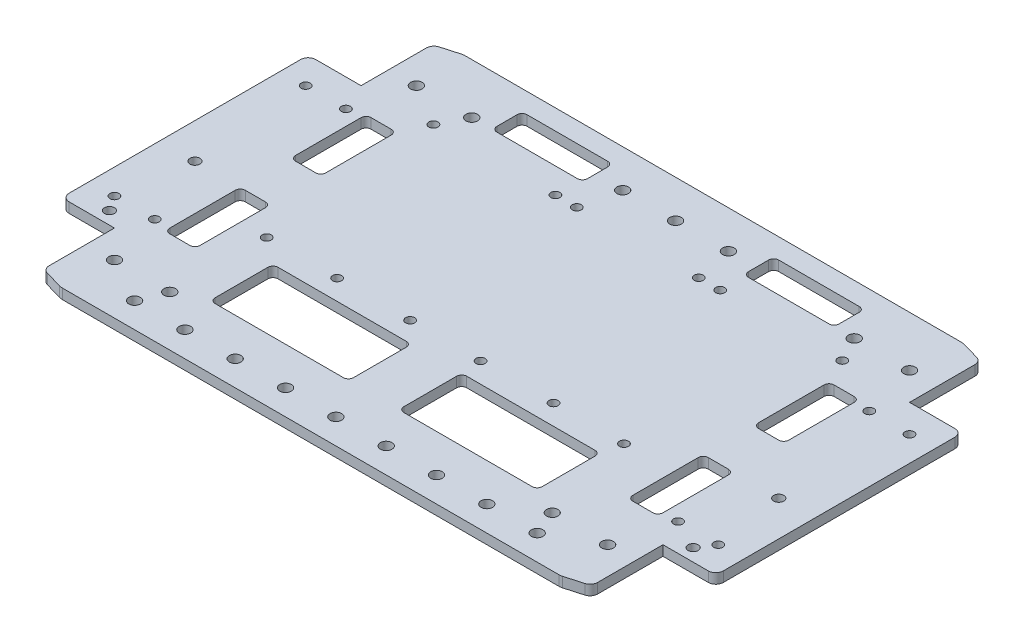
SolidWorks part; units mm, degrees
ref_plane "Plan de face" through (0, 0, 0) normal (0, 0, 1) x (1, 0, 0)
ref_plane "Plan de dessus" through (0, 0, 0) normal (0, 1, 0) x (1, 0, 0)
ref_plane "Plan de droite" through (0, 0, 0) normal (1, 0, 0) x (0, 0, -1)
sketch "Esquisse1" plane through (0, 0, 0) normal (0, 1, 0) x (1, 0, 0)
  line L0 (0, 0) -> (135, 0) construction
  line L1 (0, 0) -> (-135, 0) construction
  line L2 (-135, 0) -> (-135, -75)
  line L3 (-135, -85) -> (135, -85) construction
  line L4 (135, 0) -> (135, 75)
  line L5 (0, 85) -> (0, -85) construction
  line L6 (135, 85) -> (-135, 85) construction
  line L24 (0, -85) -> (-100, -85)
  line L26 (0, -85) -> (100, -85)
  line L28 (135, 0) -> (135, -75)
  line L31 (0, 85) -> (-100, 85)
  line L32 (0, 85) -> (100, 85)
  line L34 (-135, 0) -> (-135, 75)
  line L35 (-135, -75) -> (-100, -85)
  line L37 (-135, 75) -> (-100, 85)
  line L38 (100, 85) -> (135, 75)
  line L39 (100, -85) -> (135, -75)
  line L40 (-135, 75) -> (-100, 75) construction
  line L41 (-100, 75) -> (-100, 85) construction
  dimension "D1" = 10
  dimension "D2" = 200
  dimension "D3" = 10
  dimension "D4" = 200
  dimension "D5" = 75
  dimension "D6" = 35
  dimension "D7" = 75
  dimension "D8" = 170
extrude "Boss.-Extru.1" add sketch "Esquisse1" along normal blind 4
sketch "Esquisse15" plane through (0, 4, 0) normal (0, 1, 0) x (1, 0, 0)
  line L0 (-135, 60) -> (-135, 75)
  line L1 (-135, 60) -> (-120, 60) construction
  line L2 (-135, -60) -> (-120, -60) construction
  line L4 (-135, -60) -> (-135, -75)
  line L5 (-100, 85) -> (-135, 75) construction
  line L6 (-135, 75) -> (-135, -75) construction
  circle A0 centre (-120, 60) radius 2.3
  circle A1 centre (-120, -60) radius 2.3
extrude "Enlèv. mat.-Extru.6" cut sketch "Esquisse15" against normal up to next contours A1 | A0
mirror "Symétrie5" about plane through (0, 0, 0) normal (1, 0, 0) of "Enlèv. mat.-Extru.6"
sketch "Esquisse17" plane through (0, 4, 0) normal (0, 1, 0) x (1, 0, 0)
  line L0 (0, -85) -> (0, -71) construction
  line L1 (-100, -85) -> (100, -85) construction
  line L2 (-55, 0) -> (55, 0) construction
  line L4 (0, 85) -> (0, 71) construction
  circle A0 centre (0, -71) radius 2.3
  circle A3 centre (10, -71) radius 2.3
  circle A5 centre (-10, -71) radius 2.3
  circle A6 centre (30, -71) radius 2.3
  circle A7 centre (50, -71) radius 2.3
  circle A9 centre (90, -71) radius 2.3
  circle A11 centre (-50, -71) radius 2.3
  circle A13 centre (-90, -71) radius 2.3
  circle A14 centre (-90, 71) radius 2.3
  circle A16 centre (-50, 71) radius 2.3
  circle A17 centre (-30, 71) radius 2.3
  circle A18 centre (90, 71) radius 2.3
  circle A20 centre (50, 71) radius 2.3
  circle A21 centre (30, 71) radius 2.3
  circle A22 centre (-10, 71) radius 2.3
  circle A23 centre (10, 71) radius 2.3
  circle A24 centre (0, 71) radius 2.3
  circle A25 centre (-70, -71) radius 2.3 [skipped]
  circle A26 centre (70, -71) radius 2.3 [skipped]
  circle A27 centre (-70, -71) radius 2.3
  circle A28 centre (-30, -71) radius 2.3
  circle A29 centre (70, -71) radius 2.3
  circle A30 centre (70, 71) radius 2.3
  circle A31 centre (-70, 71) radius 2.3
  circle A32 centre (-30, -71) radius 2.3 [skipped]
  dimension "D1" = 2
  dimension "D3" = 2
  dimension "D2" = 5
  dimension "D4" = 5
  dimension "D5" = 2
  dimension "D6" = 2
  dimension "D7" = 2
  dimension "D8" = 2
sketch "Esquisse20" plane through (0, 4, 0) normal (0, 1, 0) x (1, 0, 0)
  line L0 (-120, -60) -> (-109, -60) construction
  line L1 (-109, -60) -> (-109, -82.4286)
  line L2 (-135, -75) -> (-100, -85) construction
  line L3 (-109, -60) -> (-109, -49)
  line L4 (-109, -49) -> (-135, -49)
  line L5 (-135, 75) -> (-135, -75) construction
  line L6 (-135, -49) -> (-135, -75)
  line L8 (-135, -75) -> (-109, -82.4286)
extrude "Enlèv. mat.-Extru.10" cut sketch "Esquisse20" against normal up to next
mirror "Symétrie7" about plane through (0, 0, 0) normal (1, 0, 0) of "Enlèv. mat.-Extru.10"
mirror "Symétrie8" about plane through (0, 0, 0) normal (0, 0, 1) of "Symétrie7", "Enlèv. mat.-Extru.10"
sketch "Esquisse26" plane through (0, 4, 0) normal (0, 1, 0) x (1, 0, 0)
  line L0 (135, 49) -> (130, 49)
  line L1 (109, 49) -> (135, 49) construction
  line L2 (130, 49) -> (130, -49)
  line L3 (109, -49) -> (135, -49) construction
  line L4 (130, -49) -> (135, -49)
  line L5 (135, -49) -> (135, 49)
  line L6 (-135, -49) -> (-130, -49)
  line L7 (-109, -49) -> (-135, -49) construction
  line L8 (-130, -49) -> (-130, 49)
  line L9 (-109, 49) -> (-135, 49) construction
  line L10 (-130, 49) -> (-135, 49)
  line L11 (-135, 49) -> (-135, -49)
  line L12 (100, -85) -> (109, -82.4286) construction
  line L13 (100, -85) -> (98.6264, -80.1924)
  line L14 (-100, -85) -> (100, -85)
  line L15 (107.6264, -77.621) -> (109, -77.2285)
  line L16 (-100, -85) -> (-100, -80)
  line L17 (100, -85) -> (100, -80)
  line L18 (100, -80) -> (-100, -80)
  line L19 (-109, -82.4286) -> (-107.6264, -77.621)
  line L20 (-107.6264, -77.621) -> (-98.6264, -80.1924)
  line L21 (109, -82.4286) -> (107.6264, -77.621)
  line L22 (98.6264, -80.1924) -> (107.6264, -77.621)
  line L23 (-109, -82.4286) -> (-100, -85) construction
  line L24 (-100, -85) -> (-98.6264, -80.1924)
  line L26 (109, -82.4286) -> (109, -49) construction
  line L32 (-55, 0) -> (55, 0) construction
  line L33 (-109, 77.2285) -> (-109, 82.4286)
  line L34 (-107.6264, 77.621) -> (-109, 77.2285)
  line L35 (109, 77.2285) -> (109, 82.4286)
  line L37 (-100, -85) -> (-109, -82.4286)
  line L38 (100, -85) -> (109, -82.4286)
  line L40 (100, 85) -> (109, 82.4286)
  line L45 (109, -77.2285) -> (109, -82.4286)
  line L47 (-107.6264, -77.621) -> (-109, -77.2285)
  line L48 (-109, -82.4286) -> (-109, -49) construction
  line L50 (-109, -77.2285) -> (-109, -82.4286)
  line L52 (-100, 85) -> (-109, 82.4286)
  line L55 (-100, 85) -> (-98.6264, 80.1924)
  line L56 (98.6264, 80.1924) -> (107.6264, 77.621)
  line L57 (109, 82.4286) -> (107.6264, 77.621)
  line L58 (-107.6264, 77.621) -> (-98.6264, 80.1924)
  line L59 (-109, 82.4286) -> (-107.6264, 77.621)
  line L60 (100, 80) -> (-100, 80)
  line L61 (100, 85) -> (100, 80)
  line L62 (-100, 85) -> (-100, 80)
  line L63 (107.6264, 77.621) -> (109, 77.2285)
  line L64 (-100, 85) -> (100, 85)
  line L65 (100, 85) -> (98.6264, 80.1924)
  line M92 (109, 49) -> (109, 82.4286)
  line M93 (109, 82.4286) -> (100, 85)
  line M94 (100, 85) -> (-100, 85)
  line M95 (-100, 85) -> (-109, 82.4286)
  line M96 (-109, 82.4286) -> (-109, 49)
  line M97 (-109, 49) -> (-135, 49)
  line M98 (-135, 49) -> (-135, -49)
  line M99 (-135, -49) -> (-109, -49)
  line M100 (-109, -49) -> (-109, -82.4286)
  line M101 (-109, -82.4286) -> (-100, -85)
  line M102 (-100, -85) -> (100, -85)
  line M103 (100, -85) -> (109, -82.4286)
  line M104 (109, -82.4286) -> (109, -49)
  line M105 (109, -49) -> (135, -49)
  line M106 (135, -49) -> (135, 49)
  line M107 (135, 49) -> (109, 49)
  dimension "D1" = 90
  dimension "D2" = 90
  dimension "D3" = 90
  dimension "D4" = 90
  dimension "D5" = 90
  dimension "D6" = 90
  dimension "D7" = 5
  dimension "D8" = 5
  dimension "D9" = 5
  dimension "D10" = 5
  dimension "D11" = 9.3601
extrude "Enlèv. mat.-Extru.12" cut sketch "Esquisse26" against normal up to next contours L20 L19 L16 L18 M101 | L19 L47 M100 | L24 L13 L22 L18 L20 M102 | L22 L18 L17 L21 M103 | L22 L13 L17 L18 | L21 L15 M104 | L2 M107 M105 M106 | L61 L60 L56 L57 M93 | L57 L63 M92 | L61 L65 L56 L60 | L65 L55 L58 L60 L56 M94 | L55 L62 L60 L58 | L62 L59 L58 L60 M95 | L59 L34 M96 | L8 M99 M97 M98 | L16 L24 L20 L18
fillet "Congé2" radius 3 8 edges at (109, 2, 77.2285) (-109, 2, 77.2285) (-109, 2, -77.2285) (109, 2, -77.2285) (-130, 2, -49) (-130, 2, 49) (130, 2, 49) (130, 2, -49)
fillet "Congé3" radius 5 4 edges at (99.2997, 2, 80) (-99.2997, 2, 80) (99.2997, 2, -80) (-99.2997, 2, -80)
sketch "Esquisse32" plane through (0, 4, 0) normal (0, 1, 0) x (1, 0, 0)
  line L0 (109, -60) -> (98, -60) construction
  line L2 (98, -60) -> (76, -60) construction
  line L3 (120, -60) -> (109, -60) construction
  line L4 (109, -74.9656) -> (109, -49) construction
  circle A2 centre (98, -60) radius 2.3
  circle A3 centre (76, -60) radius 2.3
  dimension "D1" = 11
  dimension "D2" = 22
extrude "Enlèv. mat.-Extru.16" cut sketch "Esquisse32" against normal up to next
mirror "Symétrie10" about plane through (0, 0, 0) normal (0, 0, 1) of "Enlèv. mat.-Extru.16"
mirror "Symétrie11" about plane through (0, 0, 0) normal (1, 0, 0) of "Symétrie10", "Enlèv. mat.-Extru.16"
sketch "Esquisse33" plane through (0, 4, 0) normal (0, 1, 0) x (1, 0, 0)
  line L0 (-109, -49) -> (-130, -49) construction
  line L1 (-130, -49) -> (-130, -39) construction
  line L2 (-130, -46) -> (-130, 46) construction
  line L3 (-130, -39) -> (-130, -15) construction
  line L4 (-130, -27) -> (-116, -27) construction
  line L5 (-116, -27) -> (-116, -44) construction
  line L6 (-116, -27) -> (-116, -10) construction
  circle A0 centre (-116, -44) radius 2
  circle A1 centre (-116, -10) radius 2
  dimension "D4" = 17
  dimension "D1" = 10
  dimension "D2" = 14
  dimension "D3" = 24
extrude "Enlèv. mat.-Extru.17" cut sketch "Esquisse33" against normal up to next
mirror "Symétrie12" about plane through (0, 0, 0) normal (1, 0, 0) of "Enlèv. mat.-Extru.17"
sketch "Esquisse34" plane through (0, 4, 0) normal (0, 1, 0) x (1, 0, 0)
  line L0 (0, 80) -> (0, 65) construction
  line L2 (98.5995, 80) -> (-98.5995, 80) construction
  line L3 (0, 65) -> (21, 65) construction
  line L4 (0, 65) -> (-21, 65) construction
  circle A0 centre (21, 65) radius 2.3
  circle A1 centre (-21, 65) radius 2.3
  circle A2 centre (0, 65) radius 2.3
  dimension "D1" = 21
  dimension "D2" = 15
  dimension "D3" = 21
extrude "Enlèv. mat.-Extru.18" cut sketch "Esquisse34" against normal up to next
sketch "Esquisse37" plane through (0, 4, 0) normal (0, 1, 0) x (1, 0, 0)
  line L0 (0, -80) -> (0, -70) construction
  line L1 (98.5995, -80) -> (-98.5995, -80) construction
  line L2 (20, -70) -> (-20, -70) construction
  line L3 (0, -55) -> (0, 55) construction
  circle A0 centre (-20, -70) radius 2.3
  circle A1 centre (-40, -70) radius 2.3
  circle A2 centre (-60, -70) radius 2.3
  circle A3 centre (-80, -70) radius 2.3
  circle A4 centre (80, -70) radius 2.3
  circle A5 centre (60, -70) radius 2.3
  circle A6 centre (40, -70) radius 2.3
  circle A7 centre (20, -70) radius 2.3
  circle A8 centre (0, -70) radius 2.3
  dimension "D1" = 20
  dimension "D3" = 80
  dimension "D2" = 4
extrude "Enlèv. mat.-Extru.21" cut sketch "Esquisse37" against normal up to next
sketch "Esquisse38" plane through (0, 4, 0) normal (0, 1, 0) x (1, 0, 0)
  line L0 (0, -80) -> (0, -55) construction
  line L1 (98.5995, -80) -> (-98.5995, -80) construction
  line L2 (10, -55) -> (-10, -55) construction
  line L3 (-10, -55) -> (-10, -30)
  line L4 (-10, -30) -> (-65, -30)
  line L5 (-65, -30) -> (-65, -55)
  line L6 (-65, -55) -> (-10, -55)
  line L7 (0, -55) -> (0, 55) construction
  line L8 (65, -55) -> (10, -55)
  line L9 (65, -30) -> (65, -55)
  line L10 (10, -30) -> (65, -30)
  line L11 (10, -55) -> (10, -30)
  dimension "D1" = 25
  dimension "D2" = 10
  dimension "D3" = 55
  dimension "D4" = 25
sketch "Esquisse39" plane through (0, 4, 0) normal (0, 1, 0) x (1, 0, 0)
  line L0 (-130, 0) -> (-120, 0) construction
  line L1 (-130, -46) -> (-130, 46) construction
  line L2 (-120, 0) -> (-120, 38) construction
  line L3 (-120, 38) -> (-104, 38) construction
  line L4 (-104, 38) -> (-104, -38) construction
  line L5 (-104, -38) -> (-120, -38) construction
  line L6 (0, -55) -> (0, 55) construction
  line L7 (104, -38) -> (120, -38) construction
  line L8 (104, 38) -> (104, -38) construction
  line L9 (120, 38) -> (104, 38) construction
  line L10 (120, 0) -> (120, 38) construction
  line L11 (130, 0) -> (120, 0) construction
  circle A0 centre (-120, 38) radius 1.8
  circle A1 centre (-104, 38) radius 1.8
  circle A2 centre (-104, -38) radius 1.8
  circle A3 centre (-120, -38) radius 1.8
  circle A4 centre (120, -38) radius 1.8
  circle A5 centre (104, -38) radius 1.8
  circle A6 centre (104, 38) radius 1.8
  circle A7 centre (120, 38) radius 1.8
extrude "Enlèv. mat.-Extru.22" cut sketch "Esquisse39" against normal up to next
sketch "Esquisse40" plane through (0, 4, 0) normal (0, 1, 0) x (1, 0, 0)
  line L0 (0, 80) -> (0, 50) construction
  line L1 (98.5995, 80) -> (-98.5995, 80) construction
  line L2 (-85.5, 50) -> (85.5, 50) construction
  line L3 (-24.25, 50) -> (24.25, 50) construction
  line L4 (24.25, 50) -> (32.75, 50) construction
  line L5 (32.75, 50) -> (81.25, 50) construction
  line L6 (0, -55) -> (0, 55) construction
  line L7 (-32.75, 50) -> (-81.25, 50) construction
  line L8 (-24.25, 50) -> (-32.75, 50) construction
  line L9 (-85.5, 50) -> (-85.5, -22) construction
  line L10 (-85.5, -22) -> (-75.5, -22) construction
  line L11 (-75.5, -22) -> (-47.5, -22) construction
  line L12 (-28.5, 50) -> (-28.5, -22) construction
  line L13 (-28.5, -22) -> (-18.5, -22) construction
  line L14 (-18.5, -22) -> (9.5, -22) construction
  line L15 (28.5, 50) -> (28.5, -22) construction
  line L16 (28.5, -22) -> (38.5, -22) construction
  line L17 (38.5, -22) -> (66.5, -22) construction
  circle A1 centre (24.25, 50) radius 1.8
  circle A2 centre (32.75, 50) radius 1.8
  circle A3 centre (81.25, 50) radius 1.8
  circle A4 centre (-81.25, 50) radius 1.8
  circle A5 centre (-32.75, 50) radius 1.8
  circle A6 centre (-24.25, 50) radius 1.8
  circle A7 centre (-75.5, -22) radius 1.8
  circle A8 centre (-47.5, -22) radius 1.8
  circle A9 centre (-18.5, -22) radius 1.8
  circle A10 centre (9.5, -22) radius 1.8
  circle A11 centre (38.5, -22) radius 1.8
  circle A12 centre (66.5, -22) radius 1.8
  dimension "D2" = 85.5
  dimension "D4" = 8.5
  dimension "D5" = 48.5
  dimension "D7" = 72
  dimension "D1" = 30
  dimension "D3" = 24.25
  dimension "D6" = 4.25
  dimension "D8" = 10
  dimension "D9" = 28
  dimension "D11" = 57
  dimension "D12" = 4.25
  dimension "D10" = 3
extrude "Enlèv. mat.-Extru.23" cut sketch "Esquisse40" against normal up to next
extrude "Enlèv. mat.-Extru.24" cut sketch "Esquisse38" against normal up to next
sketch "Esquisse41" plane through (0, 4, 0) normal (0, 1, 0) x (1, 0, 0)
  line L0 (-130, 0) -> (-98, 0) construction
  line L1 (-130, -46) -> (-130, 46) construction
  line L2 (-98, 0) -> (-86, 0) construction
  line L3 (-86, -10) -> (-86, 10) construction
  line L4 (-86, 10) -> (-98, 10)
  line L5 (-98, 10) -> (-98, 40)
  line L6 (-98, 40) -> (-86, 40)
  line L7 (-86, 40) -> (-86, 10)
  line L8 (-55, 0) -> (55, 0) construction
  line L9 (-86, -40) -> (-86, -10)
  line L10 (-98, -40) -> (-86, -40)
  line L11 (-98, -10) -> (-98, -40)
  line L12 (-86, -10) -> (-98, -10)
  dimension "D1" = 32
  dimension "D2" = 12
  dimension "D3" = 12
extrude "Enlèv. mat.-Extru.25" cut sketch "Esquisse41" against normal up to next
mirror "Symétrie13" about plane through (0, 0, 0) normal (1, 0, 0) of "Enlèv. mat.-Extru.25"
fillet "Congé4" radius 2 24 edges at (98, 2, -40) (86, 2, -40) (86, 2, -10) (98, 2, -10) (98, 2, 40) (86, 2, 40) (86, 2, 10) (98, 2, 10) (65, 2, 30) (65, 2, 55) (10, 2, 55) (10, 2, 30) (-10, 2, 30) (-10, 2, 55) (-65, 2, 55) (-65, 2, 30) (-86, 2, 10) (-98, 2, 10) (-98, 2, 40) (-86, 2, 40) (-86, 2, -10) (-86, 2, -40) (-98, 2, -10) (-98, 2, -40)
sketch "Esquisse42" plane through (0, 4, 0) normal (0, 1, 0) x (1, 0, 0)
  line L0 (50, 80) -> (-50, 80) construction
  line L1 (98.5995, 80) -> (-98.5995, 80) construction
  line L2 (-50, 80) -> (-50, 60) construction
  line L3 (-50, 60) -> (-32, 60)
  line L4 (-32, 60) -> (-32, 80) construction
  line L5 (-50, 60) -> (-68, 60)
  line L8 (0, -55) -> (0, 55) construction
  line L9 (32, 60) -> (32, 80) construction
  line L15 (-68, 60) -> (-68, 72)
  line L16 (-68, 72) -> (-32, 72)
  line L17 (-32, 72) -> (-32, 60)
  line L18 (50, 80) -> (50, 60) construction
  line L19 (32, 72) -> (32, 60)
  line L20 (68, 72) -> (32, 72)
  line L21 (68, 60) -> (68, 72)
  line L22 (50, 60) -> (68, 60)
  line L23 (50, 60) -> (32, 60)
  point P13 (0, 80)
  dimension "D1" = 50
  dimension "D2" = 18
extrude "Enlèv. mat.-Extru.26" cut sketch "Esquisse42" against normal up to next
fillet "Congé5" radius 2 8 edges at (-32, 2, -72) (-32, 2, -60) (-68, 2, -72) (-68, 2, -60) (32, 2, -60) (32, 2, -72) (68, 2, -72) (68, 2, -60)
sketch "Esquisse43" plane through (0, 4, 0) normal (0, 1, 0) x (1, 0, 0)
  line L0 (66.5, -23.8) -> (66.5, 80) construction
  line L1 (98.5995, 80) -> (-98.5995, 80) construction
  line L2 (66.5, 80) -> (62.5, 80) construction
  line L3 (9.5, -22) -> (9.5, 80) construction
  line L4 (9.5, 80) -> (5.5, 80) construction
  line L5 (-47.5, -22) -> (-47.5, 80) construction
  line L6 (-47.5, 80) -> (-51.5, 80) construction
  line L7 (0, 0) -> (0, 80) construction
  line L8 (0, 80) -> (-51.5, 80) construction
  circle A0 centre (66.5, -22) radius 1.8 construction
  dimension "D1" = 4
  dimension "D2" = 4
  dimension "D3" = 4
  dimension "D4" = 51.5
  dimension "D5" = 5.5
  dimension "D6" = 62.5
